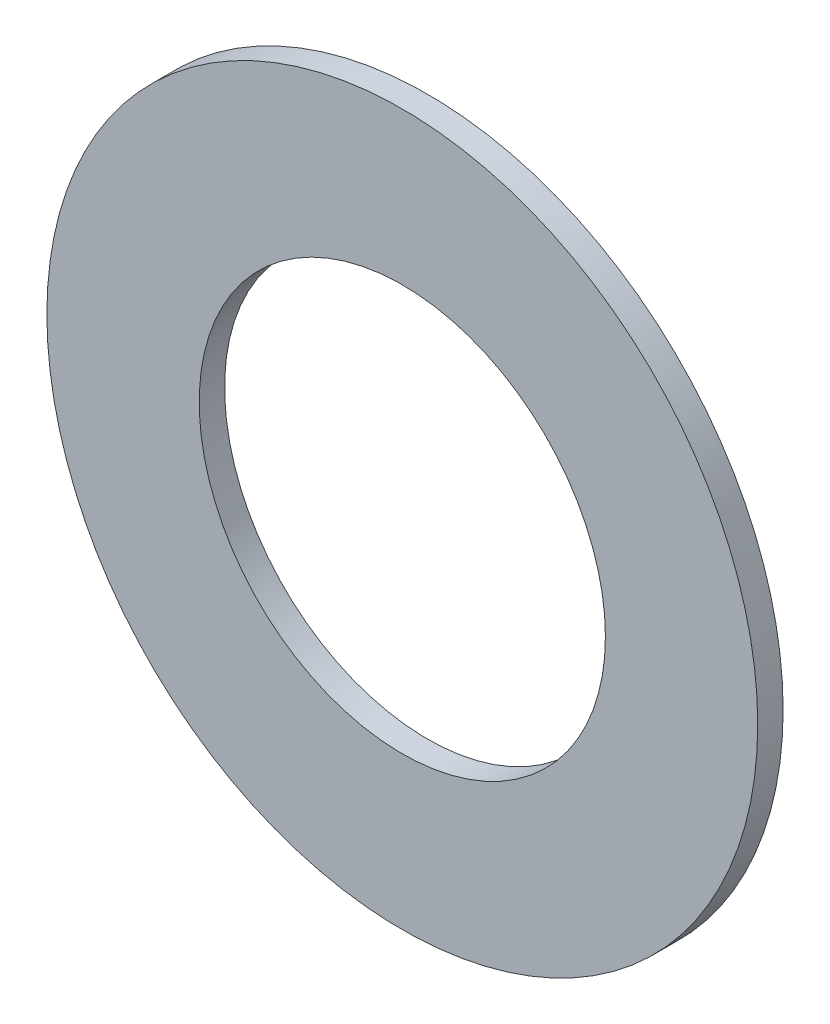
SolidWorks part; units mm, degrees
material "7075-T6 (SN)"
ref_plane "Front Plane" through (0, 0, 0) normal (0, 0, 1) x (1, 0, 0)
ref_plane "Top Plane" through (0, 0, 0) normal (0, 1, 0) x (1, 0, 0)
ref_plane "Right Plane" through (0, 0, 0) normal (1, 0, 0) x (0, 0, -1)
sketch "Sketch1" plane through (0, 0, 0) normal (0, 0, 1) x (1, 0, 0)
  circle A0 centre (0, 0) radius 14
  dimension "D1" = 28
extrude "Boss-Extrude1" add sketch "Sketch1" along normal blind 1
sketch "Sketch2" plane through (0, 0, 1) normal (0, 0, 1) x (1, 0, 0)
  circle A0 centre (0, 0) radius 8
  dimension "D1" = 16
extrude "Cut-Extrude1" cut sketch "Sketch2" against normal blind 1
